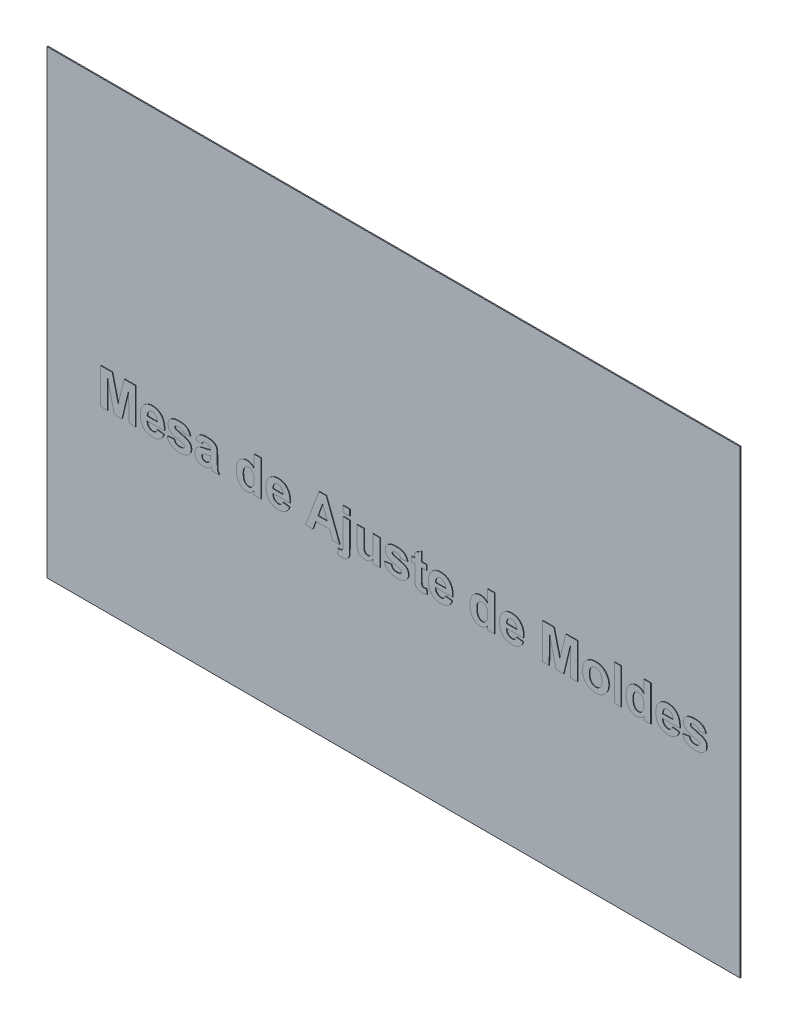
SolidWorks part; units mm, degrees
ref_plane "Alzado" through (0, 0, 0) normal (0, 0, 1) x (1, 0, 0)
ref_plane "Planta" through (0, 0, 0) normal (0, 1, 0) x (1, 0, 0)
ref_plane "Vista lateral" through (0, 0, 0) normal (1, 0, 0) x (0, 0, -1)
sketch "Croquis1" plane through (0, 0, 0) normal (0, 0, 1) x (1, 0, 0)
  line L1 (0, 0) -> (1303, 0)
  line L2 (0, 0) -> (0, -865)
  line L3 (0, -865) -> (1303, -865)
  line L4 (1303, 0) -> (1303, -865)
  dimension "D1" = 1303
  dimension "D2" = 865
extrude "Saliente-Extruir1" add sketch "Croquis1" along normal blind 1.9
sketch "Croquis2" plane through (0, 0, 1.9) normal (0, 0, 1) x (1, 0, 0)
  line L0 (95.9498, -534.661) -> (1248.2008, -534.661) construction
  text T0 "Mesa de Ajuste de Moldes" font "Arial" height in points 260
  point P3 (1248.2008, -534.661)
  point P4 (95.9498, -534.661)
extrude "Saliente-Extruir2" add sketch "Croquis2" along normal blind 1
